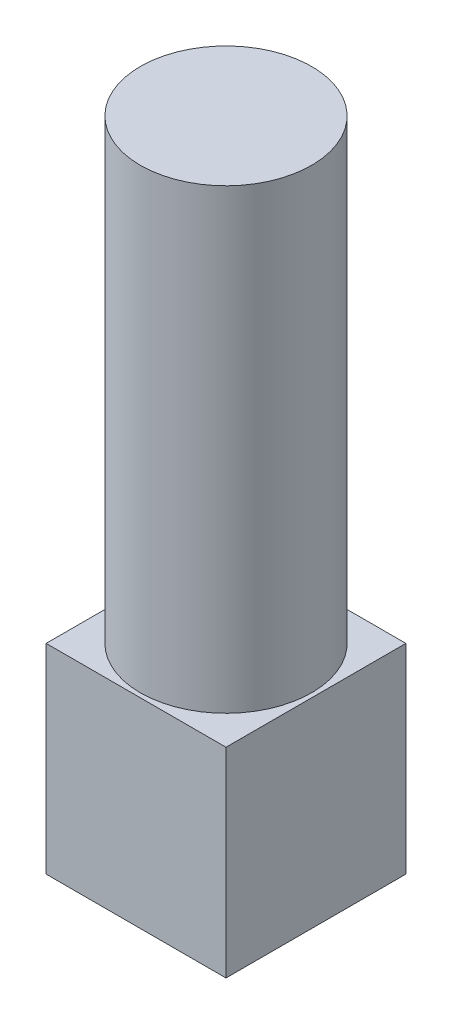
SolidWorks part; units mm, degrees
ref_plane "Front Plane" through (0, 0, 0) normal (0, 0, 1) x (1, 0, 0)
ref_plane "Top Plane" through (0, 0, 0) normal (0, 1, 0) x (1, 0, 0)
ref_plane "Right Plane" through (0, 0, 0) normal (1, 0, 0) x (0, 0, -1)
sketch "Sketch1" plane through (0, 0, 0) normal (0, 1, 0) x (1, 0, 0)
  line L1 (-64.8178, -11.9133) -> (-61.6678, -11.9133)
  line L2 (-64.8178, -11.9133) -> (-64.8178, -15.0633)
  line L3 (-64.8178, -15.0633) -> (-61.6678, -15.0633)
  line L4 (-61.6678, -11.9133) -> (-61.6678, -15.0633)
extrude "Boss-Extrude1" add sketch "Sketch1" along normal blind 3.5
sketch "Sketch3" plane through (0, 3.5, 0) normal (0, 1, 0) x (1, 0, 0)
  circle A0 centre (-63.2428, -13.4883) radius 1.5
extrude "Boss-Extrude3" add sketch "Sketch3" along normal blind 8
